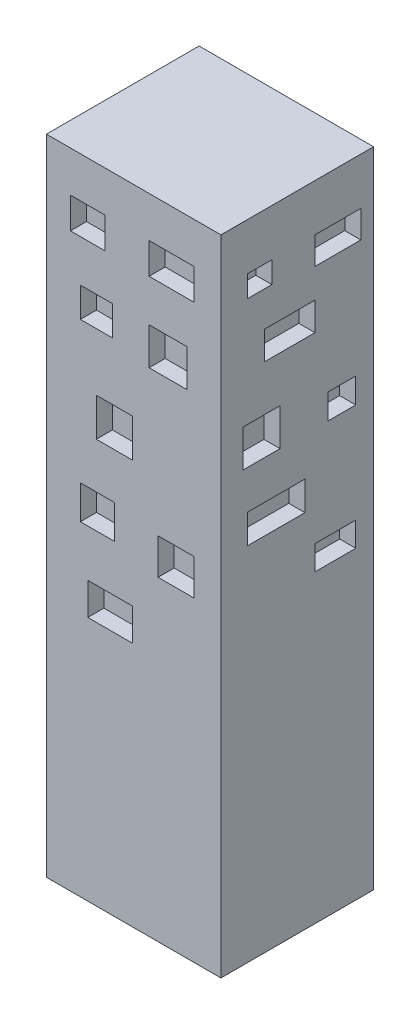
SolidWorks part; units mm, degrees
material "Кремний"
ref_plane "Front Plane" through (0, 0, 0) normal (0, 0, 1) x (1, 0, 0)
ref_plane "Top Plane" through (0, 0, 0) normal (0, 1, 0) x (1, 0, 0)
ref_plane "Right Plane" through (0, 0, 0) normal (1, 0, 0) x (0, 0, -1)
sketch "Эскиз2" plane through (0, 0, 0) normal (0, 1, 0) x (1, 0, 0)
  line L1 (0, 0) -> (-21.6865, 0)
  line L2 (0, 0) -> (0, 18.9756)
  line L3 (0, 18.9756) -> (-21.6865, 18.9756)
  line L4 (-21.6865, 0) -> (-21.6865, 18.9756)
extrude "Бобышка-Вытянуть1" add sketch "Эскиз2" along normal blind 80
sketch "Эскиз3" plane through (0, 0, 0) normal (0, 0, 1) x (1, 0, 0)
  line L1 (-18.7093, 74.9253) -> (-14.3835, 74.9253)
  line L2 (-18.7093, 74.9253) -> (-18.7093, 71.0753)
  line L3 (-18.7093, 71.0753) -> (-14.3835, 71.0753)
  line L4 (-14.3835, 74.9253) -> (-14.3835, 71.0753)
  line L5 (-8.9262, 74.9253) -> (-3.3414, 74.9253)
  line L6 (-8.9262, 74.9253) -> (-8.9262, 71.0753)
  line L7 (-8.9262, 71.0753) -> (-3.3414, 71.0753)
  line L8 (-3.3414, 74.9253) -> (-3.3414, 71.0753)
  line L9 (-17.4694, 65.8576) -> (-13.5026, 65.8576)
  line L10 (-17.4694, 65.8576) -> (-17.4694, 62.1649)
  line L11 (-17.4694, 62.1649) -> (-13.5026, 62.1649)
  line L12 (-13.5026, 65.8576) -> (-13.5026, 62.1649)
  line L13 (-8.9262, 65.8576) -> (-4.2205, 65.8576)
  line L14 (-8.9262, 65.8576) -> (-8.9262, 61.2304)
  line L15 (-8.9262, 61.2304) -> (-4.2205, 61.2304)
  line L16 (-4.2205, 65.8576) -> (-4.2205, 61.2304)
  line L17 (-15.486, 54.9974) -> (-11.0042, 54.9974)
  line L18 (-15.486, 54.9974) -> (-15.486, 50.2546)
  line L19 (-15.486, 50.2546) -> (-11.0042, 50.2546)
  line L20 (-11.0042, 54.9974) -> (-11.0042, 50.2546)
  line L21 (-17.4694, 44.5733) -> (-13.2451, 44.5733)
  line L22 (-17.4694, 44.5733) -> (-17.4694, 40.3838)
  line L23 (-17.4694, 40.3838) -> (-13.2451, 40.3838)
  line L24 (-13.2451, 44.5733) -> (-13.2451, 40.3838)
  line L25 (-7.8136, 43.7013) -> (-3.3414, 43.7013)
  line L26 (-7.8136, 43.7013) -> (-7.8136, 39.2287)
  line L27 (-7.8136, 39.2287) -> (-3.3414, 39.2287)
  line L28 (-3.3414, 43.7013) -> (-3.3414, 39.2287)
  line L29 (-16.5464, 34.5435) -> (-11.0042, 34.5435)
  line L30 (-16.5464, 34.5435) -> (-16.5464, 30.5422)
  line L31 (-16.5464, 30.5422) -> (-11.0042, 30.5422)
  line L32 (-11.0042, 34.5435) -> (-11.0042, 30.5422)
extrude "Вырез-Вытянуть1" cut sketch "Эскиз3" against normal blind 2
sketch "Эскиз4" plane through (0, 0, 0) normal (1, 0, 0) x (0, 0, -1)
  line L1 (3.3274, 74.1543) -> (6.3359, 74.1543)
  line L2 (3.3274, 74.1543) -> (3.3274, 71.4811)
  line L3 (3.3274, 71.4811) -> (6.3359, 71.4811)
  line L4 (6.3359, 74.1543) -> (6.3359, 71.4811)
  line L5 (11.6906, 74.1543) -> (17.3969, 74.1543)
  line L6 (11.6906, 74.1543) -> (11.6906, 70.7546)
  line L7 (11.6906, 70.7546) -> (17.3969, 70.7546)
  line L8 (17.3969, 74.1543) -> (17.3969, 70.7546)
  line L9 (5.3941, 67.135) -> (11.6906, 67.135)
  line L10 (5.3941, 67.135) -> (5.3941, 63.6254)
  line L11 (5.3941, 63.6254) -> (11.6906, 63.6254)
  line L12 (11.6906, 67.135) -> (11.6906, 63.6254)
  line L13 (2.7176, 57.9337) -> (7.3513, 57.9337)
  line L14 (2.7176, 57.9337) -> (2.7176, 53.3108)
  line L15 (2.7176, 53.3108) -> (7.3513, 53.3108)
  line L16 (7.3513, 57.9337) -> (7.3513, 53.3108)
  line L17 (13.3302, 56.4301) -> (16.7619, 56.4301)
  line L18 (13.3302, 56.4301) -> (13.3302, 53.3108)
  line L19 (13.3302, 53.3108) -> (16.7619, 53.3108)
  line L20 (16.7619, 56.4301) -> (16.7619, 53.3108)
  line L21 (3.3274, 48.4909) -> (10.4415, 48.4909)
  line L22 (3.3274, 48.4909) -> (3.3274, 44.8765)
  line L23 (3.3274, 44.8765) -> (10.4415, 44.8765)
  line L24 (10.4415, 48.4909) -> (10.4415, 44.8765)
  line L25 (11.6906, 40.9171) -> (16.7619, 40.9171)
  line L26 (11.6906, 40.9171) -> (11.6906, 37.8757)
  line L27 (11.6906, 37.8757) -> (16.7619, 37.8757)
  line L28 (16.7619, 40.9171) -> (16.7619, 37.8757)
extrude "Вырез-Вытянуть2" cut sketch "Эскиз4" against normal blind 2
